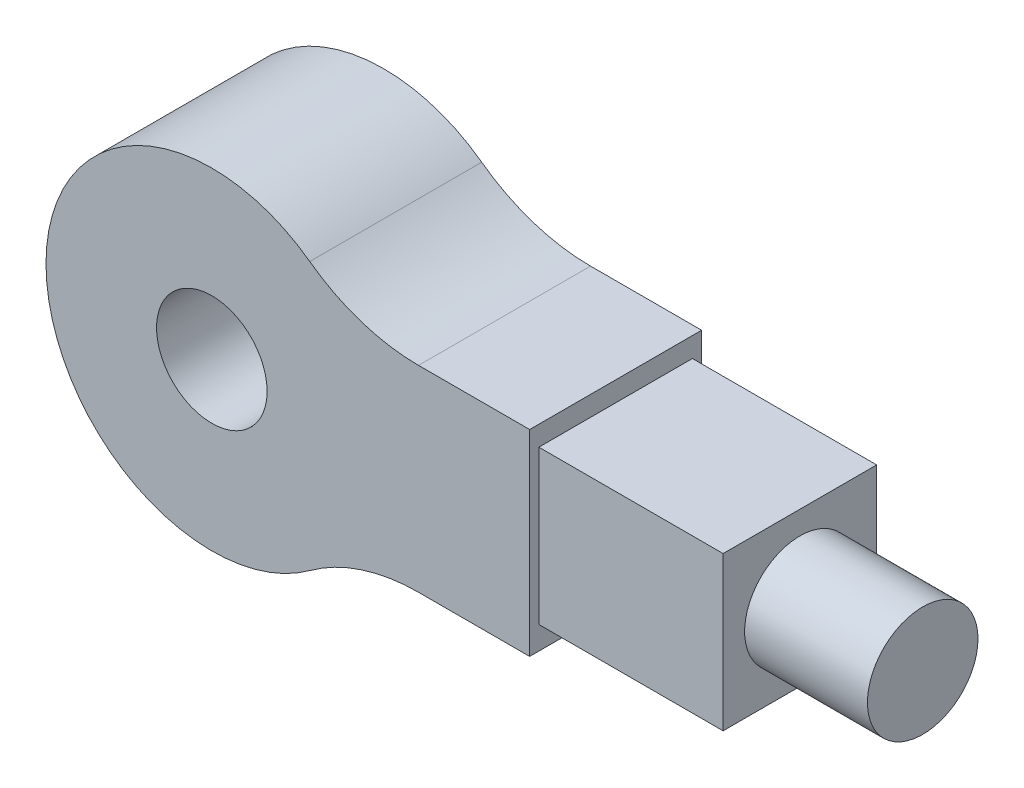
SolidWorks part; units mm, degrees
ref_plane "Front Plane" through (0, 0, 0) normal (0, 0, 1) x (1, 0, 0)
ref_plane "Top Plane" through (0, 0, 0) normal (0, 1, 0) x (1, 0, 0)
ref_plane "Right Plane" through (0, 0, 0) normal (1, 0, 0) x (0, 0, -1)
sketch "Sketch5" plane through (0, 0, 0) normal (0, 0, 1) x (1, 0, 0)
  line L0 (0, 0) -> (157.9732, 0) construction
  line L1 (33.6601, 16) -> (101.7486, 16)
  line L3 (33.6601, -16) -> (101.7486, -16)
  line L4 (101.7486, 16) -> (101.7486, -16)
  circle A0 centre (0, 0) radius 9
  arc A1 (15.9442, 21.7895) -> (15.9442, -21.7895) centre (0, 0) ccw
  arc A2 (33.6601, -16) -> (15.9442, -21.7895) centre (33.6601, -46) ccw
  arc A3 (33.6601, 16) -> (15.9442, 21.7895) centre (33.6601, 46) cw
  point P12 (21.7486, 16)
  dimension "D1" = 18
  dimension "D2" = 54
  dimension "D5" = 30
  dimension "D3" = 80
  dimension "D4" = 32
extrude "Boss-Extrude7" add sketch "Sketch5" along normal blind 28
sketch "Sketch6" plane through (101.7486, 0, 0) normal (1, 0, 0) x (0, 0, -1)
  line L0 (0, -16) -> (0, 16) construction
  circle A0 centre (-14, 0) radius 9
  dimension "D1" = 18
  dimension "D2" = 14
extrude "Cut-Extrude1" cut sketch "Sketch6" against normal blind 20 flip side to cut
sketch "Sketch7" plane through (81.7486, 0, 0) normal (1, 0, 0) x (0, 0, -1)
  line L0 (-28, -16) -> (-28, 16) construction
  line L1 (-26.5, 12.76) -> (-1.5, 12.76)
  line L2 (-26.5, 12.76) -> (-26.5, -12.24)
  line L3 (-26.5, -12.24) -> (-1.5, -12.24)
  line L4 (-1.5, 12.76) -> (-1.5, -12.24)
  dimension "D1" = 25
  dimension "D2" = 26.5
  dimension "D3" = 25
extrude "Cut-Extrude3" cut sketch "Sketch7" against normal blind 30 flip side to cut
